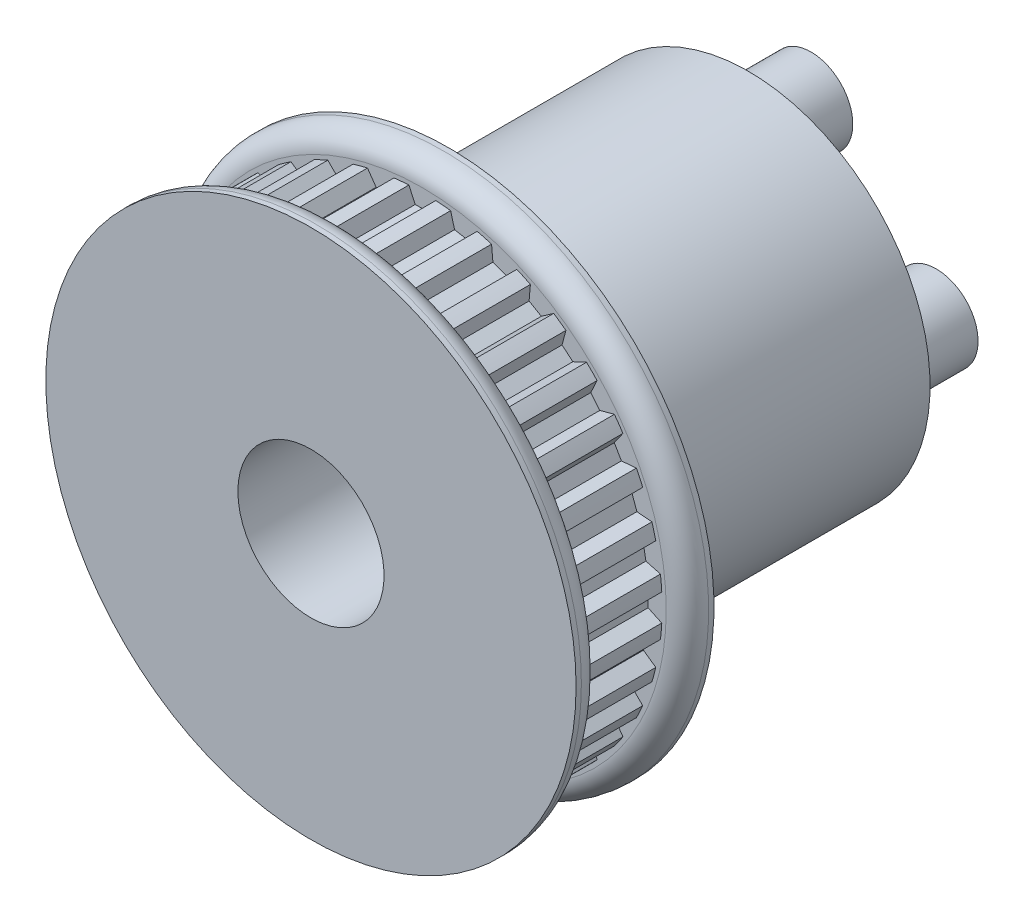
SolidWorks part; units mm, degrees
ref_plane "Front Plane" through (0, 0, 0) normal (0, 0, 1) x (1, 0, 0)
ref_plane "Top Plane" through (0, 0, 0) normal (0, 1, 0) x (1, 0, 0)
ref_plane "Right Plane" through (0, 0, 0) normal (1, 0, 0) x (0, 0, -1)
sketch "Model" plane through (0, 0, 0) normal (0, 0, 1) x (1, 0, 0)
  line L0 (10.5919, 2.2117) -> (10.7096, 1.5443)
  line L1 (11.1831, 2.6256) -> (10.5919, 2.2117)
  line L2 (10.2788, 3.3805) -> (10.9976, 3.3177)
  line L3 (10.047, 4.0174) -> (10.2788, 3.3805)
  line L4 (10.5572, 4.5277) -> (10.047, 4.0174)
  line L5 (9.5356, 5.1141) -> (10.2544, 5.177)
  line L6 (9.1967, 5.701) -> (9.5356, 5.1141)
  line L7 (9.6106, 6.2921) -> (9.1967, 5.701)
  line L8 (8.5027, 6.6922) -> (9.1997, 6.879)
  line L9 (8.067, 7.2114) -> (8.5027, 6.6922)
  line L10 (8.372, 7.8654) -> (8.067, 7.2114)
  line L11 (7.2114, 8.067) -> (7.8654, 8.372)
  line L12 (6.6922, 8.5027) -> (7.2114, 8.067)
  line L13 (6.879, 9.1997) -> (6.6922, 8.5027)
  line L14 (5.701, 9.1967) -> (6.2921, 9.6106)
  line L15 (5.1141, 9.5356) -> (5.701, 9.1967)
  line L16 (5.177, 10.2544) -> (5.1141, 9.5356)
  line L17 (4.0174, 10.047) -> (4.5277, 10.5572)
  line L18 (3.3805, 10.2788) -> (4.0174, 10.047)
  line L19 (3.3177, 10.9976) -> (3.3805, 10.2788)
  line L20 (2.2117, 10.5919) -> (2.6256, 11.1831)
  line L21 (1.5443, 10.7096) -> (2.2117, 10.5919)
  line L22 (1.3575, 11.4067) -> (1.5443, 10.7096)
  line L23 (0.3389, 10.8151) -> (0.6438, 11.4691)
  line L24 (-0.3389, 10.8151) -> (0.3389, 10.8151)
  line L25 (-0.6438, 11.4691) -> (-0.3389, 10.8151)
  line L26 (-1.5443, 10.7096) -> (-1.3575, 11.4067)
  line L27 (-2.2117, 10.5919) -> (-1.5443, 10.7096)
  line L28 (-2.6256, 11.1831) -> (-2.2117, 10.5919)
  line L29 (-3.3805, 10.2788) -> (-3.3177, 10.9976)
  line L30 (-4.0174, 10.047) -> (-3.3805, 10.2788)
  line L31 (-4.5277, 10.5572) -> (-4.0174, 10.047)
  line L32 (-5.1141, 9.5356) -> (-5.177, 10.2544)
  line L33 (-5.701, 9.1967) -> (-5.1141, 9.5356)
  line L34 (-6.2921, 9.6106) -> (-5.701, 9.1967)
  line L35 (-6.6922, 8.5027) -> (-6.879, 9.1997)
  line L36 (-7.2114, 8.067) -> (-6.6922, 8.5027)
  line L37 (-7.8654, 8.372) -> (-7.2114, 8.067)
  line L38 (-8.067, 7.2114) -> (-8.372, 7.8654)
  line L39 (-8.5027, 6.6922) -> (-8.067, 7.2114)
  line L40 (-9.1997, 6.879) -> (-8.5027, 6.6922)
  line L41 (-9.1967, 5.701) -> (-9.6106, 6.2921)
  line L42 (-9.5356, 5.1141) -> (-9.1967, 5.701)
  line L43 (-10.2544, 5.177) -> (-9.5356, 5.1141)
  line L44 (-10.047, 4.0174) -> (-10.5572, 4.5277)
  line L45 (-10.2788, 3.3805) -> (-10.047, 4.0174)
  line L46 (-10.9976, 3.3177) -> (-10.2788, 3.3805)
  line L47 (-10.5919, 2.2117) -> (-11.1831, 2.6256)
  line L48 (-10.7096, 1.5443) -> (-10.5919, 2.2117)
  line L49 (-11.4067, 1.3575) -> (-10.7096, 1.5443)
  line L50 (-10.8151, 0.3389) -> (-11.4691, 0.6438)
  line L51 (-10.8151, -0.3389) -> (-10.8151, 0.3389)
  line L52 (-11.4691, -0.6438) -> (-10.8151, -0.3389)
  line L53 (-10.7096, -1.5443) -> (-11.4067, -1.3575)
  line L54 (-10.5919, -2.2117) -> (-10.7096, -1.5443)
  line L55 (-11.1831, -2.6256) -> (-10.5919, -2.2117)
  line L56 (-10.2788, -3.3805) -> (-10.9976, -3.3177)
  line L57 (-10.047, -4.0174) -> (-10.2788, -3.3805)
  line L58 (-10.5572, -4.5277) -> (-10.047, -4.0174)
  line L59 (-9.5356, -5.1141) -> (-10.2544, -5.177)
  line L60 (-9.1967, -5.701) -> (-9.5356, -5.1141)
  line L61 (-9.6106, -6.2921) -> (-9.1967, -5.701)
  line L62 (-8.5027, -6.6922) -> (-9.1997, -6.879)
  line L63 (-8.067, -7.2114) -> (-8.5027, -6.6922)
  line L64 (-8.372, -7.8654) -> (-8.067, -7.2114)
  line L65 (-7.2114, -8.067) -> (-7.8654, -8.372)
  line L66 (-6.6922, -8.5027) -> (-7.2114, -8.067)
  line L67 (-6.879, -9.1997) -> (-6.6922, -8.5027)
  line L68 (-5.701, -9.1967) -> (-6.2921, -9.6106)
  line L69 (-5.1141, -9.5356) -> (-5.701, -9.1967)
  line L70 (-5.177, -10.2544) -> (-5.1141, -9.5356)
  line L71 (-4.0174, -10.047) -> (-4.5277, -10.5572)
  line L72 (-3.3805, -10.2788) -> (-4.0174, -10.047)
  line L73 (-3.3177, -10.9976) -> (-3.3805, -10.2788)
  line L74 (-2.2117, -10.5919) -> (-2.6256, -11.1831)
  line L75 (-1.5443, -10.7096) -> (-2.2117, -10.5919)
  line L76 (-1.3575, -11.4067) -> (-1.5443, -10.7096)
  line L77 (-0.3389, -10.8151) -> (-0.6438, -11.4691)
  line L78 (0.3389, -10.8151) -> (-0.3389, -10.8151)
  line L79 (0.6438, -11.4691) -> (0.3389, -10.8151)
  line L80 (1.5443, -10.7096) -> (1.3575, -11.4067)
  line L81 (2.2117, -10.5919) -> (1.5443, -10.7096)
  line L82 (2.6256, -11.1831) -> (2.2117, -10.5919)
  line L83 (3.3805, -10.2788) -> (3.3177, -10.9976)
  line L84 (4.0174, -10.047) -> (3.3805, -10.2788)
  line L85 (4.5277, -10.5572) -> (4.0174, -10.047)
  line L86 (5.1141, -9.5356) -> (5.177, -10.2544)
  line L87 (5.701, -9.1967) -> (5.1141, -9.5356)
  line L88 (6.2921, -9.6106) -> (5.701, -9.1967)
  line L89 (6.6922, -8.5027) -> (6.879, -9.1997)
  line L90 (7.2114, -8.067) -> (6.6922, -8.5027)
  line L91 (7.8654, -8.372) -> (7.2114, -8.067)
  line L92 (8.067, -7.2114) -> (8.372, -7.8654)
  line L93 (8.5027, -6.6922) -> (8.067, -7.2114)
  line L94 (9.1997, -6.879) -> (8.5027, -6.6922)
  line L95 (9.1967, -5.701) -> (9.6106, -6.2921)
  line L96 (9.5356, -5.1141) -> (9.1967, -5.701)
  line L97 (10.2544, -5.177) -> (9.5356, -5.1141)
  line L98 (10.047, -4.0174) -> (10.5572, -4.5277)
  line L99 (10.2788, -3.3805) -> (10.047, -4.0174)
  line L100 (10.9976, -3.3177) -> (10.2788, -3.3805)
  line L101 (10.5919, -2.2117) -> (11.1831, -2.6256)
  line L102 (10.7096, -1.5443) -> (10.5919, -2.2117)
  line L103 (11.4067, -1.3575) -> (10.7096, -1.5443)
  line L104 (10.8151, -0.3389) -> (11.4691, -0.6438)
  line L105 (10.8151, 0.3389) -> (10.8151, -0.3389)
  line L106 (11.4691, 0.6438) -> (10.8151, 0.3389)
  line L107 (10.7096, 1.5443) -> (11.4067, 1.3575)
  arc A0 (11.1831, 2.6256) -> (10.9976, 3.3177) centre (0, 0) ccw
  arc A1 (10.5572, 4.5277) -> (10.2544, 5.177) centre (0, 0) ccw
  arc A2 (9.6106, 6.2921) -> (9.1997, 6.879) centre (0, 0) ccw
  arc A3 (8.372, 7.8654) -> (7.8654, 8.372) centre (0, 0) ccw
  arc A4 (6.879, 9.1997) -> (6.2921, 9.6106) centre (0, 0) ccw
  arc A5 (5.177, 10.2544) -> (4.5277, 10.5572) centre (0, 0) ccw
  arc A6 (3.3177, 10.9976) -> (2.6256, 11.1831) centre (0, 0) ccw
  arc A7 (1.3575, 11.4067) -> (0.6438, 11.4691) centre (0, 0) ccw
  arc A8 (-0.6438, 11.4691) -> (-1.3575, 11.4067) centre (0, 0) ccw
  arc A9 (-2.6256, 11.1831) -> (-3.3177, 10.9976) centre (0, 0) ccw
  arc A10 (-4.5277, 10.5572) -> (-5.177, 10.2544) centre (0, 0) ccw
  arc A11 (-6.2921, 9.6106) -> (-6.879, 9.1997) centre (0, 0) ccw
  arc A12 (-7.8654, 8.372) -> (-8.372, 7.8654) centre (0, 0) ccw
  arc A13 (-9.1997, 6.879) -> (-9.6106, 6.2921) centre (0, 0) ccw
  arc A14 (-10.2544, 5.177) -> (-10.5572, 4.5277) centre (0, 0) ccw
  arc A15 (-10.9976, 3.3177) -> (-11.1831, 2.6256) centre (0, 0) ccw
  arc A16 (-11.4067, 1.3575) -> (-11.4691, 0.6438) centre (0, 0) ccw
  arc A17 (-11.4691, -0.6438) -> (-11.4067, -1.3575) centre (0, 0) ccw
  arc A18 (-11.1831, -2.6256) -> (-10.9976, -3.3177) centre (0, 0) ccw
  arc A19 (-10.5572, -4.5277) -> (-10.2544, -5.177) centre (0, 0) ccw
  arc A20 (-9.6106, -6.2921) -> (-9.1997, -6.879) centre (0, 0) ccw
  arc A21 (-8.372, -7.8654) -> (-7.8654, -8.372) centre (0, 0) ccw
  arc A22 (-6.879, -9.1997) -> (-6.2921, -9.6106) centre (0, 0) ccw
  arc A23 (-5.177, -10.2544) -> (-4.5277, -10.5572) centre (0, 0) ccw
  arc A24 (-3.3177, -10.9976) -> (-2.6256, -11.1831) centre (0, 0) ccw
  arc A25 (-1.3575, -11.4067) -> (-0.6438, -11.4691) centre (0, 0) ccw
  arc A26 (0.6438, -11.4691) -> (1.3575, -11.4067) centre (0, 0) ccw
  arc A27 (2.6256, -11.1831) -> (3.3177, -10.9976) centre (0, 0) ccw
  arc A28 (4.5277, -10.5572) -> (5.177, -10.2544) centre (0, 0) ccw
  arc A29 (6.2921, -9.6106) -> (6.879, -9.1997) centre (0, 0) ccw
  arc A30 (7.8654, -8.372) -> (8.372, -7.8654) centre (0, 0) ccw
  arc A31 (9.1997, -6.879) -> (9.6106, -6.2921) centre (0, 0) ccw
  arc A32 (10.2544, -5.177) -> (10.5572, -4.5277) centre (0, 0) ccw
  arc A33 (10.9976, -3.3177) -> (11.1831, -2.6256) centre (0, 0) ccw
  arc A34 (11.4067, -1.3575) -> (11.4691, -0.6438) centre (0, 0) ccw
  arc A35 (11.4691, 0.6438) -> (11.4067, 1.3575) centre (0, 0) ccw
  circle A36 centre (0, 0) radius 3.175
extrude "Boss-Extrude1" add sketch "Model" along normal blind 4.064
sketch "Sketch2" plane through (0, 0, 0) normal (0, 0, -1) x (-1, 0, 0)
  circle A0 centre (0, 0) radius 12.7
  circle A1 centre (0, 0) radius 3.175
  circle A2 centre (0, 0) radius 3.175 construction
  dimension "D1" = 25.4
extrude "Boss-Extrude2" add sketch "Sketch2" along normal blind 1.27
sketch "Sketch3" plane through (0, 0, 4.064) normal (0, 0, 1) x (1, 0, 0)
  circle A0 centre (0, 0) radius 3.175
  circle A1 centre (0, 0) radius 12.7
  circle A2 centre (0, 0) radius 3.175 construction
  dimension "D1" = 25.4
extrude "Boss-Extrude3" add sketch "Sketch3" along normal blind 1.27
fillet "Fillet1" radius 1.016 2 edges at (12.7, 0, 4.064) (-12.7, 0, 0)
sketch "Sketch5" plane through (0, 0, -1.27) normal (0, 0, -1) x (-1, 0, 0)
  circle A2 centre (0, 0) radius 8.7
  dimension "D1" = 17.4
extrude "Boss-Extrude4" add sketch "Sketch5" along normal blind 14.35
sketch "Sketch6" plane through (0, 0, -15.62) normal (0, 0, -1) x (-1, 0, 0)
  line L0 (0, 0) -> (0, 6) construction
  line L2 (6, 0) -> (0, 0) construction
  line L3 (0, 0) -> (-6, 0) construction
  line L5 (0, -6) -> (0, 0) construction
  circle A0 centre (0, 6) radius 2
  circle A1 centre (-6, 0) radius 2
  circle A2 centre (0, -6) radius 2
  circle A3 centre (6, 0) radius 2
  dimension "D2" = 4
  dimension "D1" = 6
extrude "Boss-Extrude5" add sketch "Sketch6" along normal blind 3
sketch "Sketch7" plane through (0, 0, -15.62) normal (0, 0, -1) x (-1, 0, 0)
  circle A0 centre (0, 0) radius 1.75
  dimension "D1" = 3.5
extrude "Cut-Extrude1" cut sketch "Sketch7" against normal blind 3
sketch "Sketch8" plane through (0, 0, -12.62) normal (0, 0, -1) x (-1, 0, 0)
  circle A0 centre (0, 0) radius 3.5
  dimension "D1" = 7
extrude "Cut-Extrude2" cut sketch "Sketch8" against normal through all
